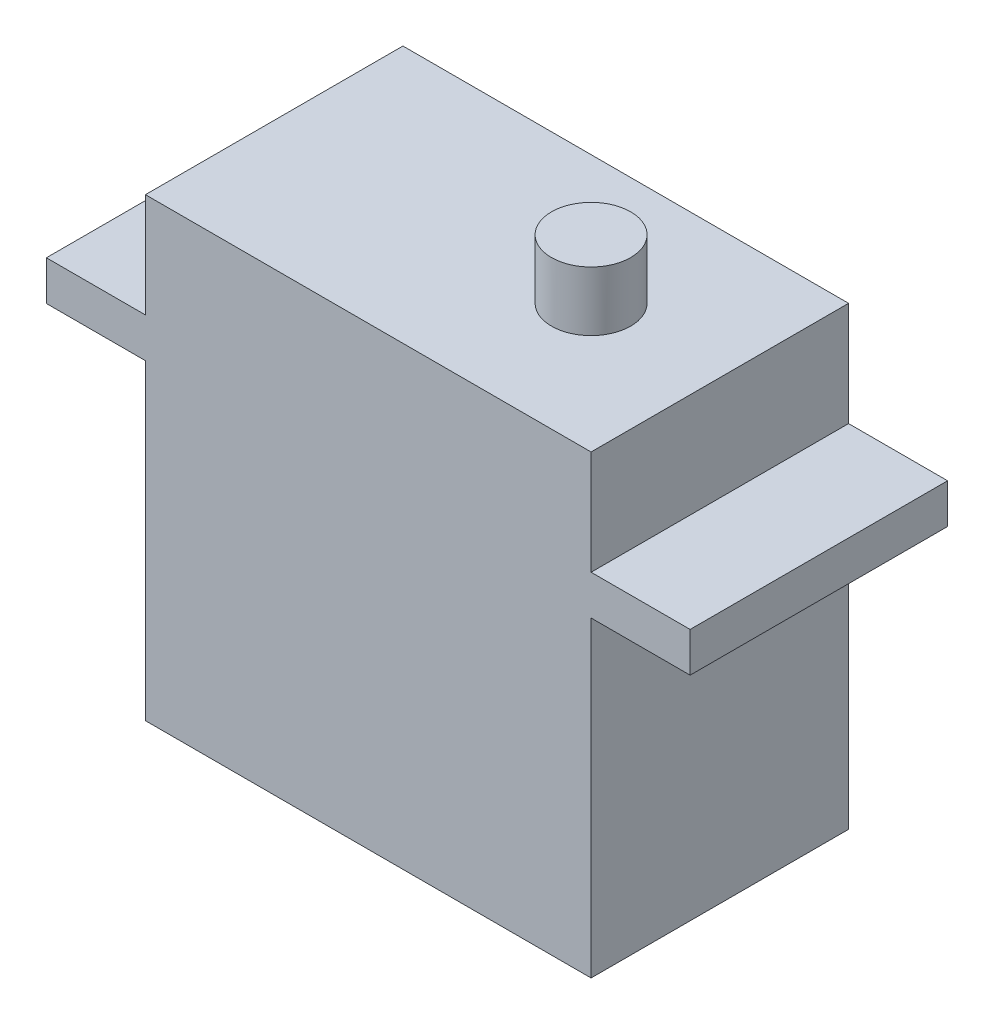
SolidWorks part; units mm, degrees
ref_plane "Plan de face" through (0, 0, 0) normal (0, 0, 1) x (1, 0, 0)
ref_plane "Plan de dessus" through (0, 0, 0) normal (0, 1, 0) x (1, 0, 0)
ref_plane "Plan de droite" through (0, 0, 0) normal (1, 0, 0) x (0, 0, -1)
sketch "Esquisse1" plane through (0, 0, 0) normal (0, 0, 1) x (1, 0, 0)
  line L0 (-30.9036, 29.7093) -> (-30.9036, 24.4503)
  line L1 (-30.9036, 29.7093) -> (-8.4036, 29.7093)
  line L2 (-30.9036, 24.4503) -> (-35.9036, 24.4503)
  line L3 (-30.9036, 6.7093) -> (-8.4036, 6.7093)
  line L4 (-35.9036, 24.4503) -> (-35.9036, 22.4503)
  line L5 (-35.9036, 22.4503) -> (-30.9036, 22.4503)
  line L6 (-30.9036, 22.4503) -> (-30.9036, 6.7093)
  line L7 (-8.4036, 29.7093) -> (-8.4036, 24.4503)
  line L8 (-8.4036, 24.4503) -> (-3.4036, 24.4503)
  line L9 (-3.4036, 24.4503) -> (-3.4036, 22.4503)
  line L10 (-3.4036, 22.4503) -> (-8.4036, 22.4503)
  line L11 (-8.4036, 22.4503) -> (-8.4036, 6.7093)
  dimension "D1" = 22.5
  dimension "D2" = 23
  dimension "D3" = 2
  dimension "D4" = 5
  dimension "D5" = 5
extrude "Extrusion1" add sketch "Esquisse1" along normal blind 13
sketch "Esquisse2" plane through (0, 29.7093, 0) normal (0, 1, 0) x (1, 0, 0)
  line L0 (-8.4036, 0) -> (-30.9036, 0) construction
  line L1 (-8.4036, -13) -> (-8.4036, 0) construction
  circle A0 centre (-14.9036, -6.5) radius 2
  dimension "D3" = 4
  dimension "D2" = 6.5
  dimension "D1" = 6.5
extrude "Extrusion2" add sketch "Esquisse2" along normal blind 3
